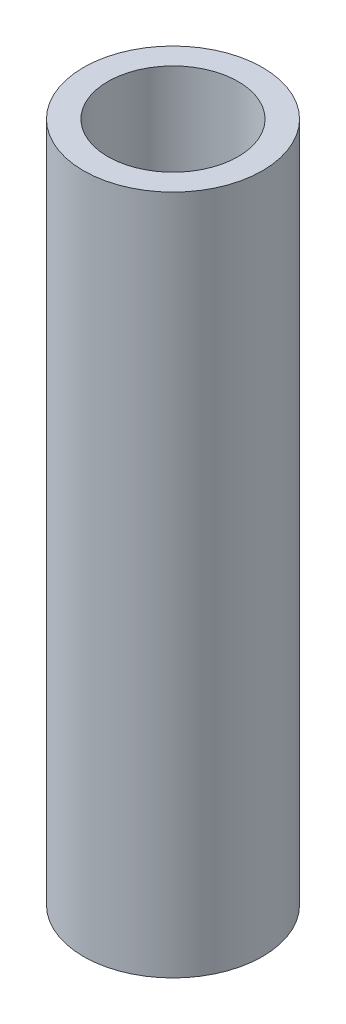
SolidWorks part; units mm, degrees
ref_plane "Front Plane" through (0, 0, 0) normal (0, 0, 1) x (1, 0, 0)
ref_plane "Top Plane" through (0, 0, 0) normal (0, 1, 0) x (1, 0, 0)
ref_plane "Right Plane" through (0, 0, 0) normal (1, 0, 0) x (0, 0, -1)
sketch "Sketch1" plane through (0, 0, 0) normal (0, 1, 0) x (1, 0, 0)
  circle A0 centre (0, 0) radius 24.3078
  circle A1 centre (0, 0) radius 33.401
extrude "Boss-Extrude1" add sketch "Sketch1" along normal mid plane 254
